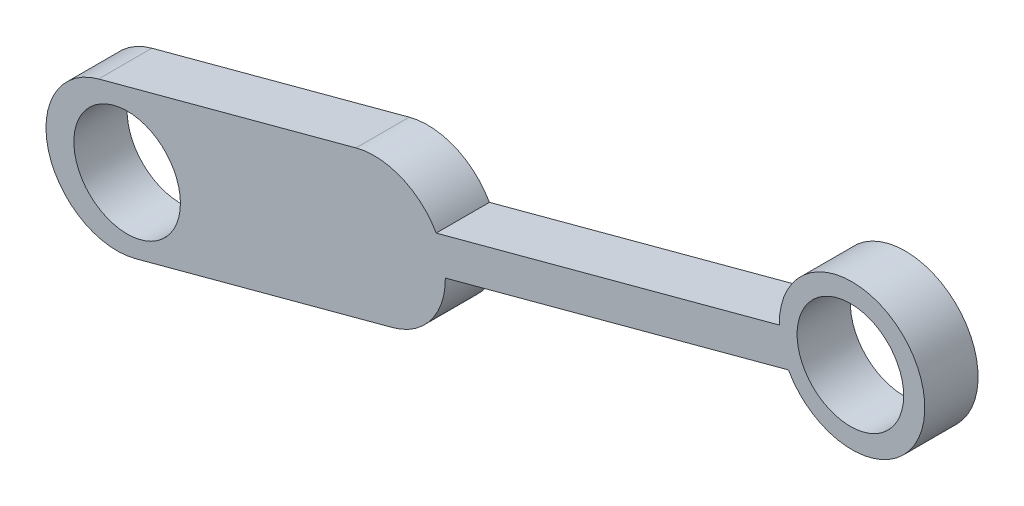
SolidWorks part; units mm, degrees
ref_plane "Front Plane" through (0, 0, 0) normal (0, 0, 1) x (1, 0, 0)
ref_plane "Top Plane" through (0, 0, 0) normal (0, 1, 0) x (1, 0, 0)
ref_plane "Right Plane" through (0, 0, 0) normal (1, 0, 0) x (0, 0, -1)
sketch "Sketch1" plane through (0, 0, 0) normal (0, 0, 1) x (1, 0, 0)
  line L51 (-130.8441, 34.2492) -> (-116.3552, 38.1315)
  line L52 (-128.7735, 26.5218) -> (-114.2846, 30.404)
  line L53 (-111.8377, 36.2361) -> (-92.5192, 41.4125)
  line L54 (-111.3201, 34.3042) -> (-92.0016, 39.4806)
  arc A46 (-92.0016, 39.4806) -> (-92.5192, 41.4125) centre (-88.4218, 41.4751) ccw
  arc A47 (-130.8441, 34.2492) -> (-128.7735, 26.5218) centre (-129.8088, 30.3855) ccw
  arc A48 (-114.2846, 30.404) -> (-111.3201, 34.3042) centre (-115.3199, 34.2677) ccw
  arc A51 (-111.8377, 36.2361) -> (-116.3552, 38.1315) centre (-115.3199, 34.2677) ccw
extrude "Boss-Extrude2" add sketch "Sketch1" along normal blind 3 contours A46 L53 A51 L51 A47 L52 A48 L54
sketch "Sketch2" plane through (0, 0, 3) normal (0, 0, 1) x (1, 0, 0)
  circle A0 centre (-88.5146, 41.4687) radius 3
  circle A1 centre (-129.2395, 30.4898) radius 3
  point P4 (-129.2395, 30.4898)
extrude "Cut-Extrude1" cut sketch "Sketch2" against normal blind 3
